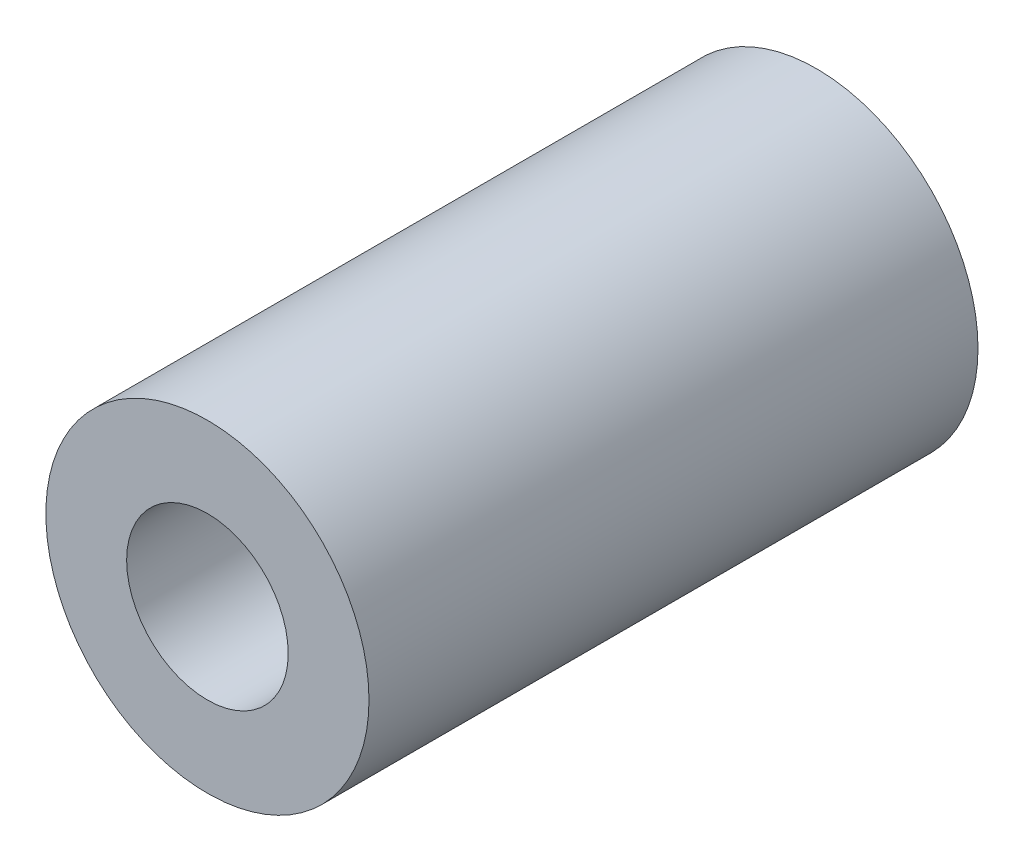
SolidWorks part; units mm, degrees
ref_plane "Front" through (0, 0, 0) normal (0, 0, 1) x (1, 0, 0)
ref_plane "Top" through (0, 0, 0) normal (0, 1, 0) x (1, 0, 0)
ref_plane "Right" through (0, 0, 0) normal (1, 0, 0) x (0, 0, -1)
sketch "Sketch1" plane through (0, 0, 0) normal (0, 0, 1) x (1, 0, 0)
  circle A0 centre (0, 0) radius 13
  circle A1 centre (0, 0) radius 6.5
  dimension "D1" = 26
  dimension "D2" = 13
extrude "Extrude1" add sketch "Sketch1" along normal blind 49
